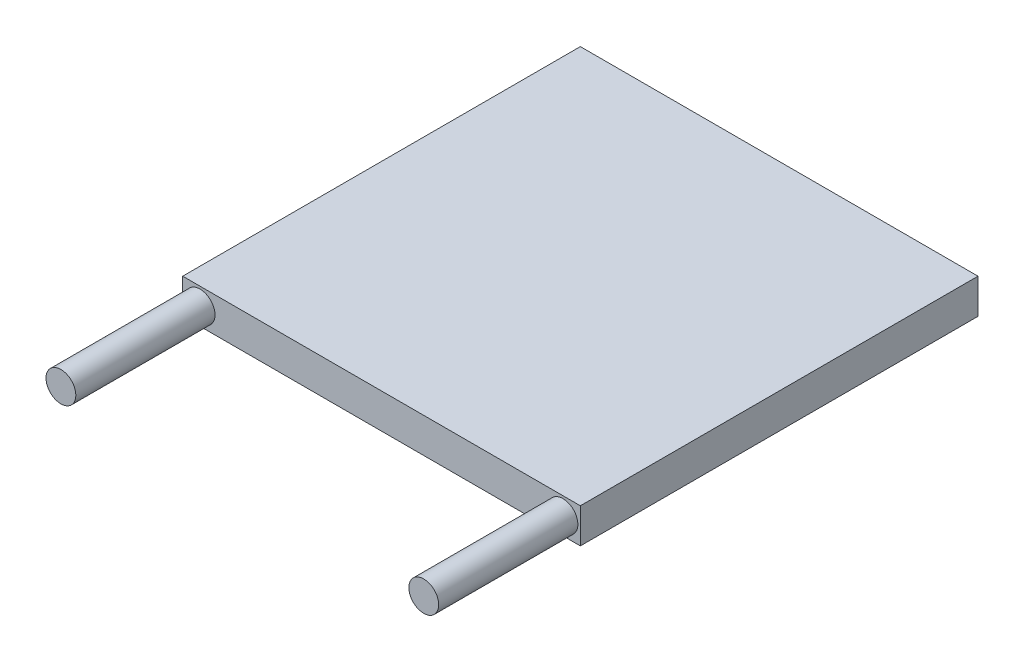
SolidWorks part; units mm, degrees
ref_plane "Front Plane" through (0, 0, 0) normal (0, 0, 1) x (1, 0, 0)
ref_plane "Top Plane" through (0, 0, 0) normal (0, 1, 0) x (1, 0, 0)
ref_plane "Right Plane" through (0, 0, 0) normal (1, 0, 0) x (0, 0, -1)
sketch "Sketch1" plane through (0, 0, 0) normal (0, 1, 0) x (1, 0, 0)
  line L1 (-20, -20) -> (20, -20)
  line L2 (-20, -20) -> (-20, 20)
  line L3 (-20, 20) -> (20, 20)
  line L4 (20, -20) -> (20, 20)
  line L5 (-20, -20) -> (20, 20) construction
  line L6 (-20, 20) -> (20, -20) construction
  point P0 (0, 0)
  dimension "D1" = 40
  dimension "D2" = 40
extrude "Boss-Extrude1" add sketch "Sketch1" along normal blind 3.5
sketch "Sketch2" plane through (0, 0, 20) normal (0, 0, 1) x (1, 0, 0)
  line L0 (-20, 3.5) -> (-20, 0) construction
  line L1 (-20, 0) -> (20, 0) construction
  line L2 (0, 0) -> (0, 3.5)
  line L3 (-20, 3.5) -> (20, 3.5) construction
  circle A0 centre (-18.25, 1.75) radius 1.5
  circle A1 centre (18.25, 1.75) radius 1.5
  dimension "D3" = 3
  dimension "D1" = 1.75
  dimension "D2" = 1.75
extrude "Boss-Extrude2" add sketch "Sketch2" along normal blind 14 contours A1 | A0
